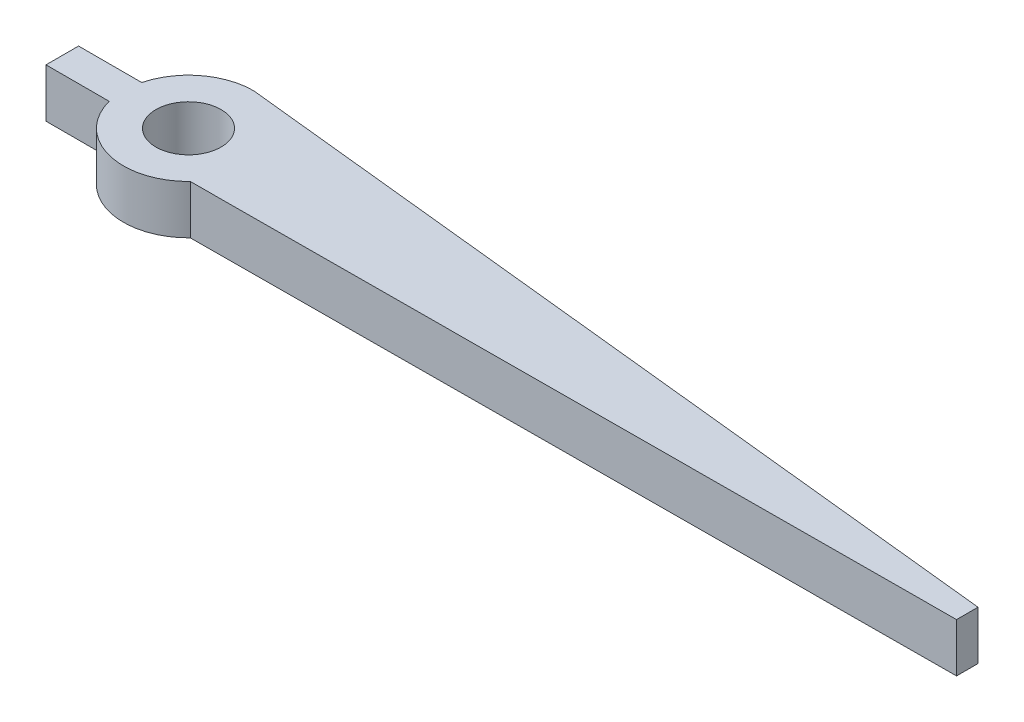
SolidWorks part; units mm, degrees
ref_plane "Front Plane" through (0, 0, 0) normal (0, 0, 1) x (1, 0, 0)
ref_plane "Top Plane" through (0, 0, 0) normal (0, 1, 0) x (1, 0, 0)
ref_plane "Right Plane" through (0, 0, 0) normal (1, 0, 0) x (0, 0, -1)
sketch "Sketch1" plane through (0, 0, 0) normal (0, 1, 0) x (1, 0, 0)
  line L0 (-40.4796, 15.6729) -> (-40.4796, 16.1729)
  line L1 (-40.4796, 15.6729) -> (-40.4796, 15.1729)
  line L2 (-44.3561, 16.1729) -> (-44.3561, 15.1729)
  line L3 (-42.4161, 15.1729) -> (-44.3561, 15.1729)
  line L4 (-42.4161, 16.1729) -> (-44.3561, 16.1729)
  line L5 (-40.4796, 17.6729) -> (-15.6165, 15.0597)
  line L6 (-15.6165, 15.0597) -> (-15.6165, 14.4007)
  line L7 (-39.0385, 14.2861) -> (-15.6165, 14.4007)
  circle A0 centre (-40.4796, 15.6729) radius 1
  circle A1 centre (-40.4796, 15.6729) radius 2
extrude "Boss-Extrude1" add sketch "Sketch1" along normal blind 1.5 contours A1 L7 L6 L5 | A1 L5 A0 | A1 L4 L2 L3
